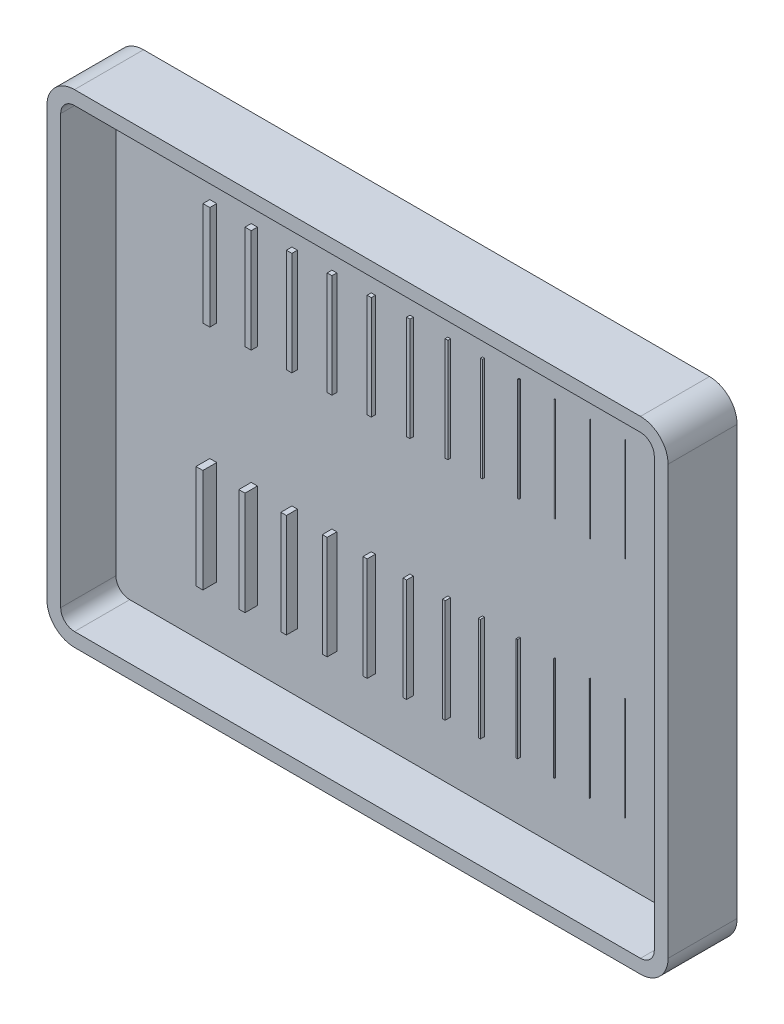
SolidWorks part; units mm, degrees
ref_plane "Front Plane" through (0, 0, 0) normal (0, 0, 1) x (1, 0, 0)
ref_plane "Top Plane" through (0, 0, 0) normal (0, 1, 0) x (1, 0, 0)
ref_plane "Right Plane" through (0, 0, 0) normal (1, 0, 0) x (0, 0, -1)
sketch "Sketch1" plane through (0, 0, 0) normal (0, 0, 1) x (1, 0, 0)
  line L1 (0, 0) -> (90, 0)
  line L2 (0, 0) -> (0, 70)
  line L3 (0, 70) -> (90, 70)
  line L4 (90, 0) -> (90, 70)
  dimension "D1" = 90
  dimension "D2" = 70
extrude "Boss-Extrude1" add sketch "Sketch1" along normal blind 10
fillet "Fillet1" radius 4 4 edges at (0, 0, 5) (0, 70, 5) (90, 0, 5) (90, 70, 5)
shell "Shell1" thickness 2
sketch "Sketch2" plane through (0, 0, 2) normal (0, 0, 1) x (1, 0, 0)
  line L0 (86, 68) -> (4, 68) construction
  line L1 (15.6, 58) -> (16.6, 58)
  line L2 (15.6, 58) -> (15.6, 43)
  line L3 (15.6, 43) -> (16.6, 43)
  line L4 (16.6, 58) -> (16.6, 43)
  line L5 (2, 66) -> (2, 4) construction
  dimension "D1" = 15
  dimension "D2" = 10
  dimension "D3" = 13.6
  dimension "D4" = 1
extrude "Boss-Extrude2" add sketch "Sketch2" along normal blind 1
sketch "Sketch3" plane through (0, 0, 2) normal (0, 0, 1) x (1, 0, 0)
  line L0 (16.6, 43) -> (16.6, 58) construction
  line L1 (21.6, 58) -> (22.5, 58)
  line L2 (21.6, 58) -> (21.6, 43)
  line L3 (21.6, 43) -> (22.5, 43)
  line L4 (22.5, 58) -> (22.5, 43)
  line L5 (86, 68) -> (4, 68) construction
  dimension "D1" = 5
  dimension "D2" = 0.9
  dimension "D3" = 10
  dimension "D4" = 15
extrude "Boss-Extrude3" add sketch "Sketch3" along normal blind 0.9
sketch "Sketch4" plane through (0, 0, 2) normal (0, 0, 1) x (1, 0, 0)
  line L0 (22.5, 43) -> (22.5, 58) construction
  line L1 (27.5, 58) -> (28.3, 58)
  line L2 (27.5, 58) -> (27.5, 43)
  line L3 (27.5, 43) -> (28.3, 43)
  line L4 (28.3, 58) -> (28.3, 43)
  line L5 (86, 68) -> (4, 68) construction
  dimension "D1" = 0.8
  dimension "D2" = 15
  dimension "D3" = 5
  dimension "D4" = 10
extrude "Boss-Extrude4" add sketch "Sketch4" along normal blind 0.8
sketch "Sketch5" plane through (0, 0, 2) normal (0, 0, 1) x (1, 0, 0)
  line L0 (28.3, 43) -> (28.3, 58) construction
  line L1 (33.3, 58) -> (34, 58)
  line L2 (33.3, 58) -> (33.3, 43)
  line L3 (33.3, 43) -> (34, 43)
  line L4 (34, 58) -> (34, 43)
  line L5 (86, 68) -> (4, 68) construction
  dimension "D1" = 0.7
  dimension "D2" = 15
  dimension "D3" = 5
  dimension "D4" = 10
extrude "Boss-Extrude5" add sketch "Sketch5" along normal blind 0.7
sketch "Sketch6" plane through (0, 0, 2) normal (0, 0, 1) x (1, 0, 0)
  line L0 (86, 68) -> (4, 68) construction
  line L1 (39, 58) -> (39.6, 58)
  line L2 (39, 58) -> (39, 43)
  line L3 (39, 43) -> (39.6, 43)
  line L4 (39.6, 58) -> (39.6, 43)
  line L5 (34, 43) -> (34, 58) construction
  dimension "D1" = 0.6
  dimension "D2" = 15
  dimension "D3" = 10
  dimension "D4" = 5
extrude "Boss-Extrude6" add sketch "Sketch6" along normal blind 0.6
sketch "Sketch7" plane through (0, 0, 2) normal (0, 0, 1) x (1, 0, 0)
  line L0 (39.6, 43) -> (39.6, 58) construction
  line L1 (44.6, 58) -> (45.1, 58)
  line L2 (44.6, 58) -> (44.6, 43)
  line L3 (44.6, 43) -> (45.1, 43)
  line L4 (45.1, 58) -> (45.1, 43)
  line L5 (86, 68) -> (4, 68) construction
  dimension "D1" = 0.5
  dimension "D2" = 15
  dimension "D3" = 5
  dimension "D4" = 10
extrude "Boss-Extrude7" add sketch "Sketch7" along normal blind 0.5
sketch "Sketch8" plane through (0, 0, 2) normal (0, 0, 1) x (1, 0, 0)
  line L0 (45.1, 43) -> (45.1, 58) construction
  line L1 (50.1, 58) -> (50.5, 58)
  line L2 (50.1, 58) -> (50.1, 43)
  line L3 (50.1, 43) -> (50.5, 43)
  line L4 (50.5, 58) -> (50.5, 43)
  line L5 (86, 68) -> (4, 68) construction
  dimension "D1" = 0.4
  dimension "D2" = 15
  dimension "D3" = 5
  dimension "D4" = 10
extrude "Boss-Extrude8" add sketch "Sketch8" along normal blind 0.4
sketch "Sketch9" plane through (0, 0, 2) normal (0, 0, 1) x (1, 0, 0)
  line L0 (86, 68) -> (4, 68) construction
  line L1 (55.1, 58) -> (55.4, 58)
  line L2 (55.1, 58) -> (55.1, 43)
  line L3 (55.1, 43) -> (55.4, 43)
  line L4 (55.4, 58) -> (55.4, 43)
  line L5 (50.1, 58) -> (50.1, 43) construction
  dimension "D1" = 10
  dimension "D2" = 15
  dimension "D3" = 5
  dimension "D4" = 0.3
extrude "Boss-Extrude9" add sketch "Sketch9" along normal blind 0.3
sketch "Sketch10" plane through (0, 0, 2) normal (0, 0, 1) x (1, 0, 0)
  line L0 (55.4, 43) -> (55.4, 58) construction
  line L1 (60.4, 58) -> (60.6, 58)
  line L2 (60.4, 58) -> (60.4, 43)
  line L3 (60.4, 43) -> (60.6, 43)
  line L4 (60.6, 58) -> (60.6, 43)
  line L5 (86, 68) -> (4, 68) construction
  dimension "D1" = 15
  dimension "D2" = 0.2
  dimension "D3" = 5
  dimension "D4" = 10
extrude "Boss-Extrude10" add sketch "Sketch10" along normal blind 0.2
sketch "Sketch11" plane through (0, 0, 2) normal (0, 0, 1) x (1, 0, 0)
  line L1 (65.7, 43) -> (65.6, 43)
  line L2 (65.7, 43) -> (65.7, 58)
  line L3 (65.7, 58) -> (65.6, 58)
  line L4 (65.6, 43) -> (65.6, 58)
  dimension "D1" = 0.1
  dimension "D2" = 15
  dimension "D3" = 5
extrude "Boss-Extrude11" add sketch "Sketch11" along normal blind 0.1
sketch "Sketch12" plane through (0, 0, 2) normal (0, 0, 1) x (1, 0, 0)
  line L1 (70.775, 43) -> (70.7, 43)
  line L2 (70.775, 43) -> (70.775, 58)
  line L3 (70.775, 58) -> (70.7, 58)
  line L4 (70.7, 43) -> (70.7, 58)
  dimension "D1" = 0.075
  dimension "D2" = 15
  dimension "D3" = 5
extrude "Boss-Extrude12" add sketch "Sketch12" along normal blind 0.075
sketch "Sketch14" plane through (0, 0, 2) normal (0, 0, 1) x (1, 0, 0)
  line L1 (75.825, 43) -> (75.775, 43)
  line L2 (75.825, 43) -> (75.825, 58)
  line L3 (75.825, 58) -> (75.775, 58)
  line L4 (75.775, 43) -> (75.775, 58)
  dimension "D1" = 15
  dimension "D2" = 0.05
  dimension "D3" = 5
extrude "Boss-Extrude13" add sketch "Sketch14" along normal blind 0.05
sketch "Sketch15" plane through (0, 0, 2) normal (0, 0, 1) x (1, 0, 0)
  line L1 (15.6, 25.5132) -> (16.6, 25.5132)
  line L2 (15.6, 25.5132) -> (15.6, 10.5132)
  line L3 (15.6, 10.5132) -> (16.6, 10.5132)
  line L4 (16.6, 25.5132) -> (16.6, 10.5132)
  dimension "D1" = 15
  dimension "D2" = 1
extrude "Boss-Extrude14" add sketch "Sketch15" along normal blind 2
sketch "Sketch17" plane through (0, 0, 2) normal (0, 0, 1) x (1, 0, 0)
  line L1 (21.6, 25.5132) -> (22.5, 25.5132)
  line L2 (21.6, 25.5132) -> (21.6, 10.5132)
  line L3 (21.6, 10.5132) -> (22.5, 10.5132)
  line L4 (22.5, 25.5132) -> (22.5, 10.5132)
  dimension "D1" = 15
  dimension "D2" = 0.9
extrude "Boss-Extrude15" add sketch "Sketch17" along normal blind 1.8
sketch "Sketch18" plane through (0, 0, 2) normal (0, 0, 1) x (1, 0, 0)
  line L1 (27.5, 25.5132) -> (28.3, 25.5132)
  line L2 (27.5, 25.5132) -> (27.5, 10.5132)
  line L3 (27.5, 10.5132) -> (28.3, 10.5132)
  line L4 (28.3, 25.5132) -> (28.3, 10.5132)
  dimension "D1" = 15
  dimension "D2" = 0.8
extrude "Boss-Extrude16" add sketch "Sketch18" along normal blind 1.6
sketch "Sketch19" plane through (0, 0, 2) normal (0, 0, 1) x (1, 0, 0)
  line L1 (33.3, 25.5132) -> (34, 25.5132)
  line L2 (33.3, 25.5132) -> (33.3, 10.5132)
  line L3 (33.3, 10.5132) -> (34, 10.5132)
  line L4 (34, 25.5132) -> (34, 10.5132)
  dimension "D1" = 15
  dimension "D2" = 0.7
extrude "Boss-Extrude17" add sketch "Sketch19" along normal blind 1.4
sketch "Sketch20" plane through (0, 0, 2) normal (0, 0, 1) x (1, 0, 0)
  line L1 (39, 25.5132) -> (39.6, 25.5132)
  line L2 (39, 25.5132) -> (39, 10.5132)
  line L3 (39, 10.5132) -> (39.6, 10.5132)
  line L4 (39.6, 25.5132) -> (39.6, 10.5132)
  dimension "D1" = 15
  dimension "D2" = 0.6
extrude "Boss-Extrude18" add sketch "Sketch20" along normal blind 1.2
sketch "Sketch21" plane through (0, 0, 2) normal (0, 0, 1) x (1, 0, 0)
  line L1 (44.6, 25.5132) -> (45.1, 25.5132)
  line L2 (44.6, 25.5132) -> (44.6, 10.5132)
  line L3 (44.6, 10.5132) -> (45.1, 10.5132)
  line L4 (45.1, 25.5132) -> (45.1, 10.5132)
  dimension "D1" = 15
  dimension "D2" = 0.5
extrude "Boss-Extrude19" add sketch "Sketch21" along normal blind 1
sketch "Sketch22" plane through (0, 0, 2) normal (0, 0, 1) x (1, 0, 0)
  line L1 (50.1, 25.5132) -> (50.5, 25.5132)
  line L2 (50.1, 25.5132) -> (50.1, 10.5132)
  line L3 (50.1, 10.5132) -> (50.5, 10.5132)
  line L4 (50.5, 25.5132) -> (50.5, 10.5132)
  dimension "D1" = 15
  dimension "D2" = 0.4
extrude "Boss-Extrude20" add sketch "Sketch22" along normal blind 0.8
sketch "Sketch23" plane through (0, 0, 2) normal (0, 0, 1) x (1, 0, 0)
  line L1 (55.1, 25.5132) -> (55.4, 25.5132)
  line L2 (55.1, 25.5132) -> (55.1, 10.5132)
  line L3 (55.1, 10.5132) -> (55.4, 10.5132)
  line L4 (55.4, 25.5132) -> (55.4, 10.5132)
  dimension "D1" = 15
  dimension "D2" = 0.3
extrude "Boss-Extrude21" add sketch "Sketch23" along normal blind 0.6
sketch "Sketch24" plane through (0, 0, 2) normal (0, 0, 1) x (1, 0, 0)
  line L1 (60.4, 25.5132) -> (60.6, 25.5132)
  line L2 (60.4, 25.5132) -> (60.4, 10.5132)
  line L3 (60.4, 10.5132) -> (60.6, 10.5132)
  line L4 (60.6, 25.5132) -> (60.6, 10.5132)
  dimension "D1" = 15
  dimension "D2" = 0.2
extrude "Boss-Extrude22" add sketch "Sketch24" along normal blind 0.4
sketch "Sketch25" plane through (0, 0, 2) normal (0, 0, 1) x (1, 0, 0)
  line L1 (65.6, 25.5132) -> (65.7, 25.5132)
  line L2 (65.6, 25.5132) -> (65.6, 10.5132)
  line L3 (65.6, 10.5132) -> (65.7, 10.5132)
  line L4 (65.7, 25.5132) -> (65.7, 10.5132)
  dimension "D1" = 15
  dimension "D2" = 0.1
extrude "Boss-Extrude23" add sketch "Sketch25" along normal blind 0.2
sketch "Sketch27" plane through (0, 0, 2) normal (0, 0, 1) x (1, 0, 0)
  line L1 (70.7, 25.5132) -> (70.775, 25.5132)
  line L2 (70.7, 25.5132) -> (70.7, 10.5132)
  line L3 (70.7, 10.5132) -> (70.775, 10.5132)
  line L4 (70.775, 25.5132) -> (70.775, 10.5132)
  dimension "D1" = 15
  dimension "D2" = 0.075
extrude "Boss-Extrude24" add sketch "Sketch27" along normal blind 0.15
sketch "Sketch28" plane through (0, 0, 2) normal (0, 0, 1) x (1, 0, 0)
  line L1 (75.775, 25.5132) -> (75.825, 25.5132)
  line L2 (75.775, 25.5132) -> (75.775, 10.5132)
  line L3 (75.775, 10.5132) -> (75.825, 10.5132)
  line L4 (75.825, 25.5132) -> (75.825, 10.5132)
  dimension "D1" = 15
  dimension "D2" = 0.05
extrude "Boss-Extrude25" add sketch "Sketch28" along normal blind 0.1
